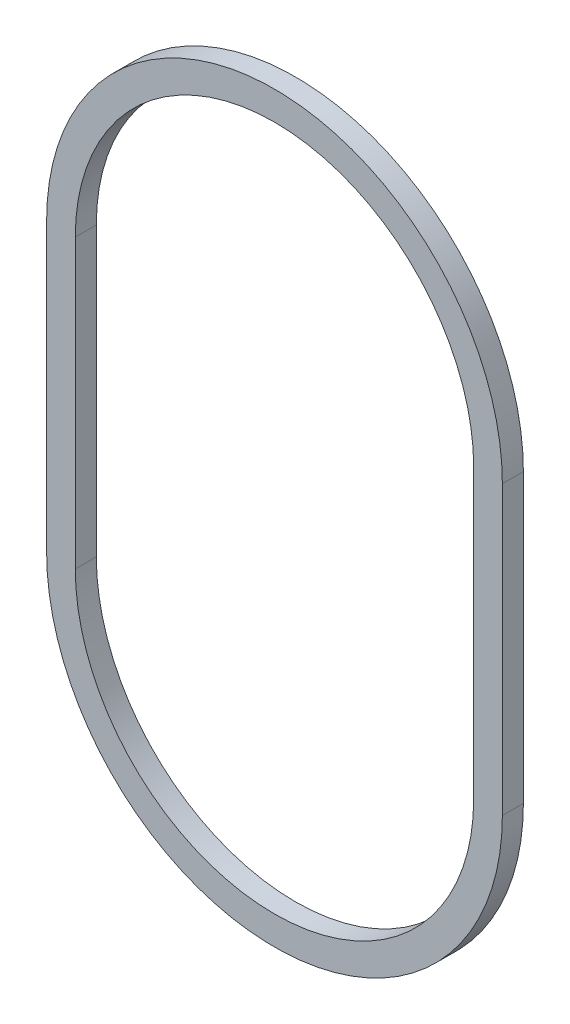
SolidWorks part; units mm, degrees
ref_plane "Ön Düzlem" through (0, 0, 0) normal (0, 0, 1) x (1, 0, 0)
ref_plane "Üst Düzlem" through (0, 0, 0) normal (0, 1, 0) x (1, 0, 0)
ref_plane "Sağ Düzlem" through (0, 0, 0) normal (1, 0, 0) x (0, 0, -1)
sketch "Çizim1" plane through (0, 0, 0) normal (0, 0, 1) x (1, 0, 0)
  line L0 (-20.85, 15.04) -> (-20.85, -15.04)
  line L1 (20.85, -15.04) -> (20.85, 15.04)
  line L2 (23.85, -15.04) -> (23.85, 15.04)
  line L3 (-23.85, 15.04) -> (-23.85, -15.04)
  arc A0 (23.85, 15.04) -> (-23.85, 15.04) centre (0, 15.04) ccw
  arc A1 (23.85, -15.04) -> (-23.85, -15.04) centre (0, -15.04) cw
  arc A2 (20.85, 15.04) -> (-20.85, 15.04) centre (0, 15.04) ccw
  arc A3 (20.85, -15.04) -> (-20.85, -15.04) centre (0, -15.04) cw
  dimension "D2" = 47.7
  dimension "D1" = 3
extrude "Yükseklik-Ekstrüzyon1" add sketch "Çizim1" along normal mid plane 2.2
